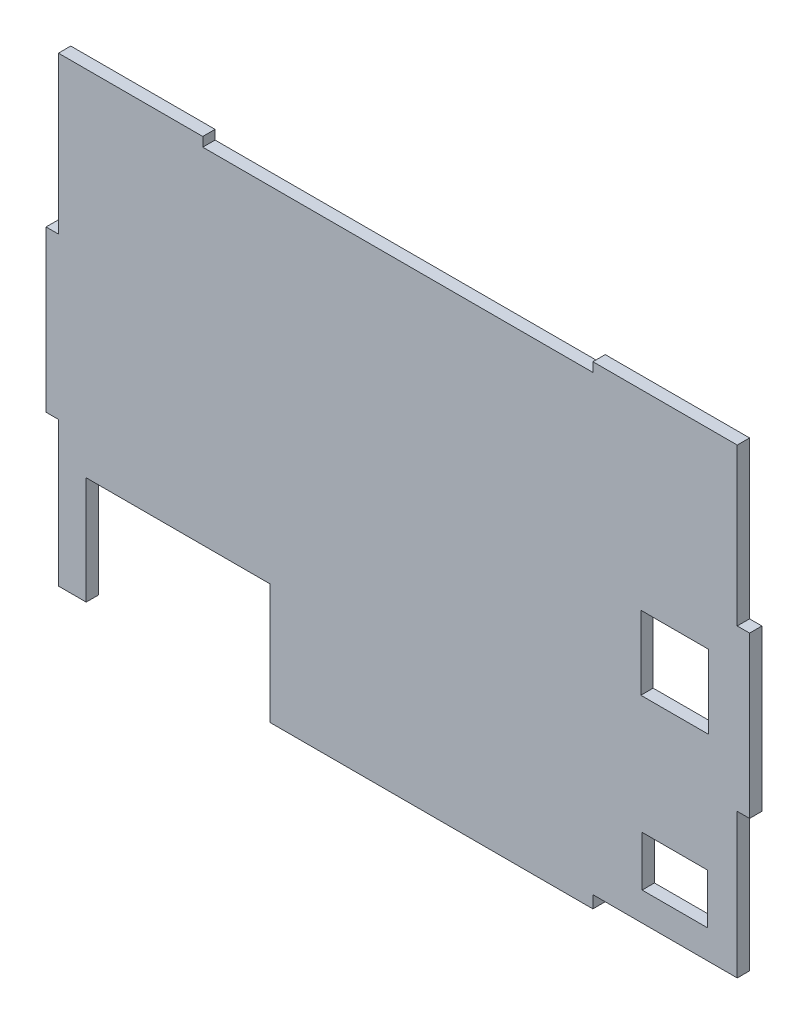
SolidWorks part; units mm, degrees
ref_plane "Front Plane" through (0, 0, 0) normal (0, 0, 1) x (1, 0, 0)
ref_plane "Top Plane" through (0, 0, 0) normal (0, 1, 0) x (1, 0, 0)
ref_plane "Right Plane" through (0, 0, 0) normal (1, 0, 0) x (0, 0, -1)
sketch "Sketch1" plane through (0, 0, 0) normal (0, 0, 1) x (1, 0, 0)
  line L1 (-17.5301, -39.851) -> (34.848, -39.851)
  line L2 (-53.798, -14.451) -> (-53.798, 11.5707)
  line L4 (60.248, -14.451) -> (60.248, 11.5707)
  line L5 (-51.798, 11.5707) -> (-51.798, 35.465)
  line L6 (-51.798, -37.851) -> (-51.798, 35.465) construction
  line L7 (58.248, -37.851) -> (58.248, -14.451)
  line L8 (-51.798, -37.851) -> (-47.2898, -37.851)
  line L9 (-51.798, -37.851) -> (-51.798, -14.451)
  line L10 (-28.398, 36.9707) -> (-28.398, 35.465)
  line L11 (34.848, 36.9707) -> (34.848, 35.465)
  line L12 (-53.798, 11.5707) -> (-51.798, 11.5707)
  line L13 (-53.798, -14.451) -> (-51.798, -14.451)
  line L14 (-53.798, 37.465) -> (60.248, 37.465) construction
  line L15 (-53.798, -39.851) -> (-53.798, 37.465) construction
  line L16 (-53.798, -39.851) -> (60.248, -39.851) construction
  line L17 (60.248, -39.851) -> (60.248, 37.465) construction
  line L19 (-51.798, 35.465) -> (58.248, 35.465) construction
  line L20 (58.248, 11.5707) -> (58.248, 35.465)
  line L21 (34.848, -37.851) -> (34.848, -39.851)
  line L22 (58.248, 11.5707) -> (60.248, 11.5707)
  line L23 (58.248, -14.451) -> (60.248, -14.451)
  line L24 (58.248, -37.851) -> (58.248, 35.465) construction
  line L25 (34.848, -37.851) -> (58.248, -37.851)
  line L27 (-51.798, -37.851) -> (58.248, -37.851) construction
  line L28 (34.848, 36.9707) -> (58.248, 36.9707)
  line L29 (-28.398, 35.465) -> (34.848, 35.465)
  line L30 (-51.798, 35.465) -> (-51.798, 36.9707)
  line L31 (-51.798, 36.9707) -> (-28.398, 36.9707)
  line L32 (58.248, 35.465) -> (58.248, 36.9707)
  line L34 (-17.5301, -20.3947) -> (-47.2898, -20.3947)
  line L35 (-17.5301, -20.3947) -> (-17.5301, -39.851)
  line L37 (-47.2898, -20.3947) -> (-47.2898, -37.851)
  line L38 (53.5587, 5.9707) -> (42.6173, 5.9707)
  line L39 (53.5587, 5.9707) -> (53.5587, -5.9707)
  line L40 (53.5587, -5.9707) -> (42.6173, -5.9707)
  line L41 (42.6173, 5.9707) -> (42.6173, -5.9707)
  line L42 (53.4216, -25.1107) -> (42.8288, -25.1107)
  line L43 (53.4216, -25.1107) -> (53.4216, -33.2154)
  line L44 (53.4216, -33.2154) -> (42.8288, -33.2154)
  line L45 (42.8288, -25.1107) -> (42.8288, -33.2154)
  point P80 (48.088, 0)
  point P83 (48.088, -29.6574)
  point P107 (-29.1849, -29.1229)
  dimension "D1" = 114.046
  dimension "D4" = 76.8217
  dimension "D5" = 25.4
  dimension "D6" = 25.4
  dimension "D7" = 25.4
  dimension "D8" = 52.3781
  dimension "D9" = 25.4
  dimension "D18" = 11.9414
  dimension "D20" = 10.9414
  dimension "D23" = 10.5928
  dimension "D30" = 8.1047
  dimension "D31" = 19.4563
  dimension "D21" = 22.6131
  dimension "D36" = 10.7282
  dimension "D38" = 29.7597
  dimension "D3" = 2
extrude "Boss-Extrude1" add sketch "Sketch1" along normal blind 2
